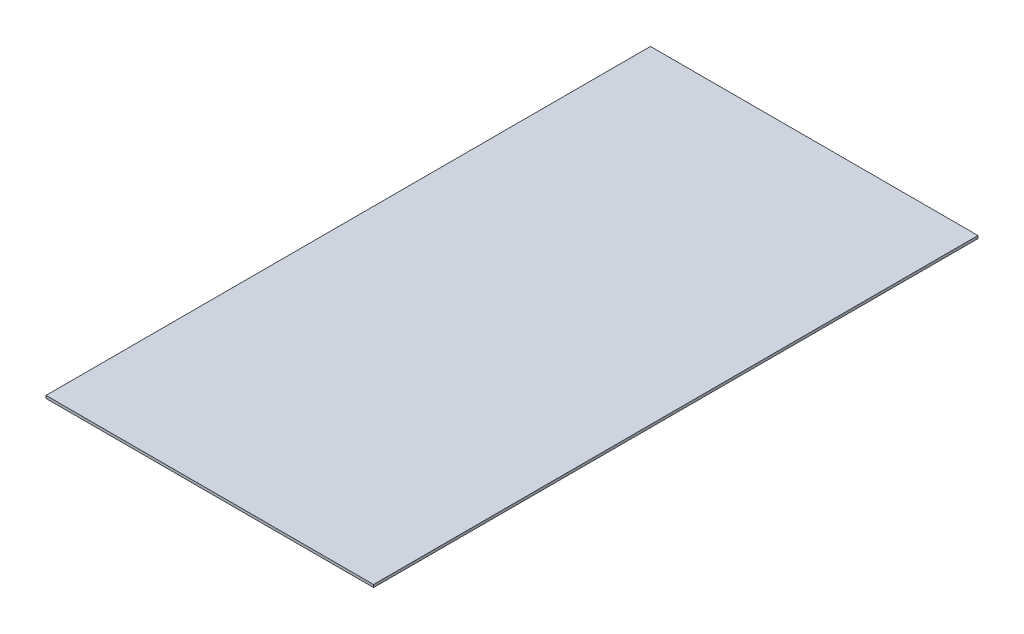
SolidWorks part; units mm, degrees
material "Epoxy, Unfilled"
ref_plane "Front Plane" through (0, 0, 0) normal (0, 0, 1) x (1, 0, 0)
ref_plane "Top Plane" through (0, 0, 0) normal (0, 1, 0) x (1, 0, 0)
ref_plane "Right Plane" through (0, 0, 0) normal (1, 0, 0) x (0, 0, -1)
sketch "Sketch1" plane through (0, 0, 0) normal (0, 1, 0) x (1, 0, 0)
  line L1 (0, 0) -> (22, 0)
  line L2 (0, 0) -> (0, 40.6)
  line L3 (0, 40.6) -> (22, 40.6)
  line L4 (22, 0) -> (22, 40.6)
extrude "Boss-Extrude1" add sketch "Sketch1" along normal blind 0.18
